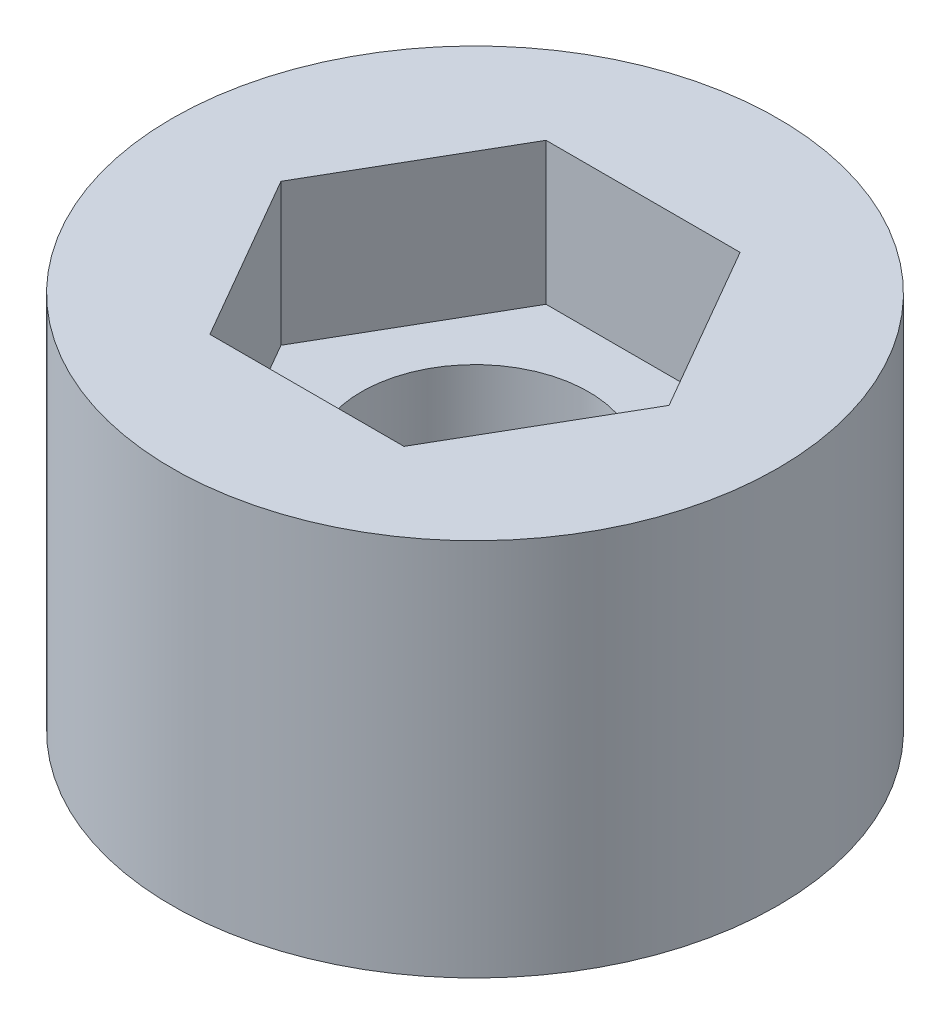
SolidWorks part; units mm, degrees
ref_plane "Front Plane" through (0, 0, 0) normal (0, 0, 1) x (1, 0, 0)
ref_plane "Top Plane" through (0, 0, 0) normal (0, 1, 0) x (1, 0, 0)
ref_plane "Right Plane" through (0, 0, 0) normal (1, 0, 0) x (0, 0, -1)
sketch "Sketch1" plane through (0, 0, 0) normal (0, 1, 0) x (1, 0, 0)
  circle A0 centre (0, 0) radius 2.4
  dimension "D1" = 4.8
extrude "Extrude-Thin1" add sketch "Sketch1" along normal blind 8 thin
sketch "Sketch2" plane through (0, 8, 0) normal (0, 1, 0) x (1, 0, 0)
  line L1 (4.0992, 0) -> (2.0496, 3.55)
  line L2 (2.0496, 3.55) -> (-2.0496, 3.55)
  line L3 (-2.0496, 3.55) -> (-4.0992, 0)
  line L4 (-4.0992, 0) -> (-2.0496, -3.55)
  line L5 (-2.0496, -3.55) -> (2.0496, -3.55)
  line L6 (2.0496, -3.55) -> (4.0992, 0)
  circle A0 centre (0, 0) radius 3.55 construction
  dimension "D1" = 7.1
extrude "Cut-Extrude1" cut sketch "Sketch2" against normal blind 3
